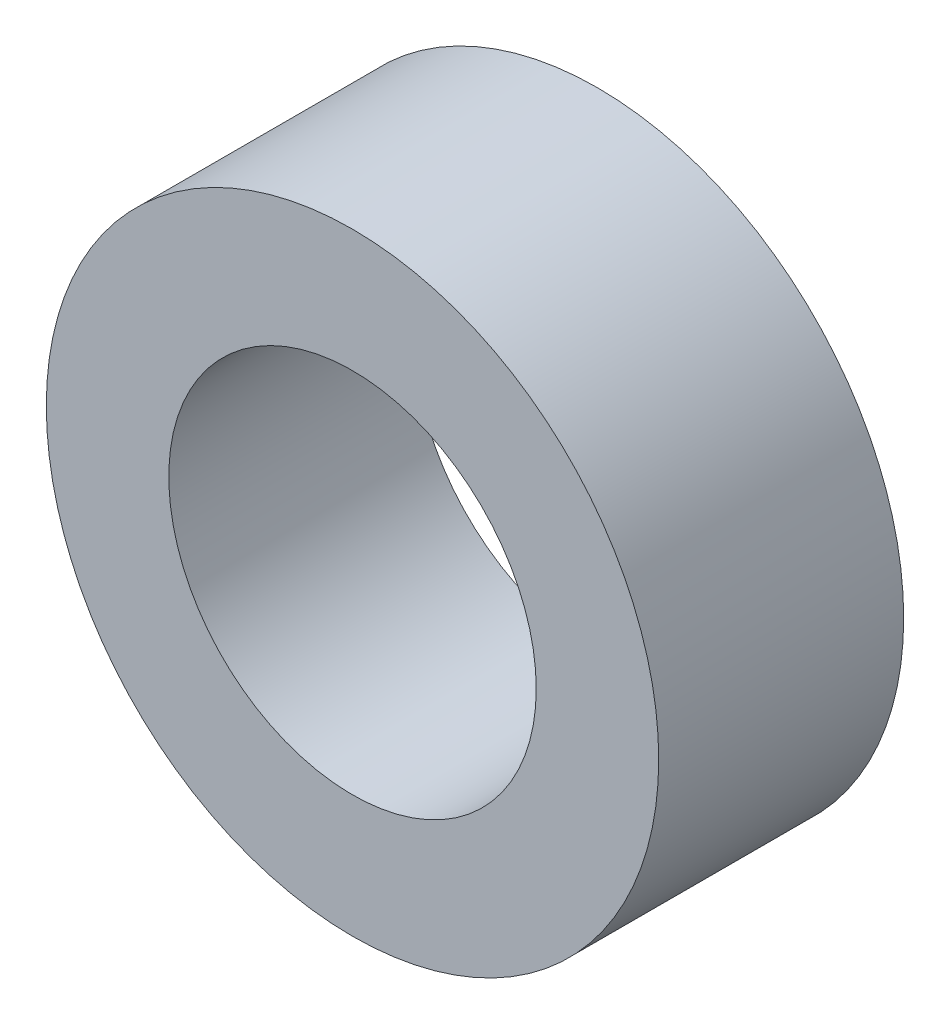
SolidWorks part; units mm, degrees
ref_plane "Front Plane" through (0, 0, 0) normal (0, 0, 1) x (1, 0, 0)
ref_plane "Top Plane" through (0, 0, 0) normal (0, 1, 0) x (1, 0, 0)
ref_plane "Right Plane" through (0, 0, 0) normal (1, 0, 0) x (0, 0, -1)
sketch "Sketch1" plane through (0, 0, 0) normal (0, 0, 1) x (1, 0, 0)
  circle A0 centre (0, 0) radius 9.525
  circle A1 centre (0, 0) radius 15.875
  dimension "D1" = 6.35
  dimension "D2" = 9.525
extrude "Boss-Extrude1" add sketch "Sketch1" along normal blind 12.7
